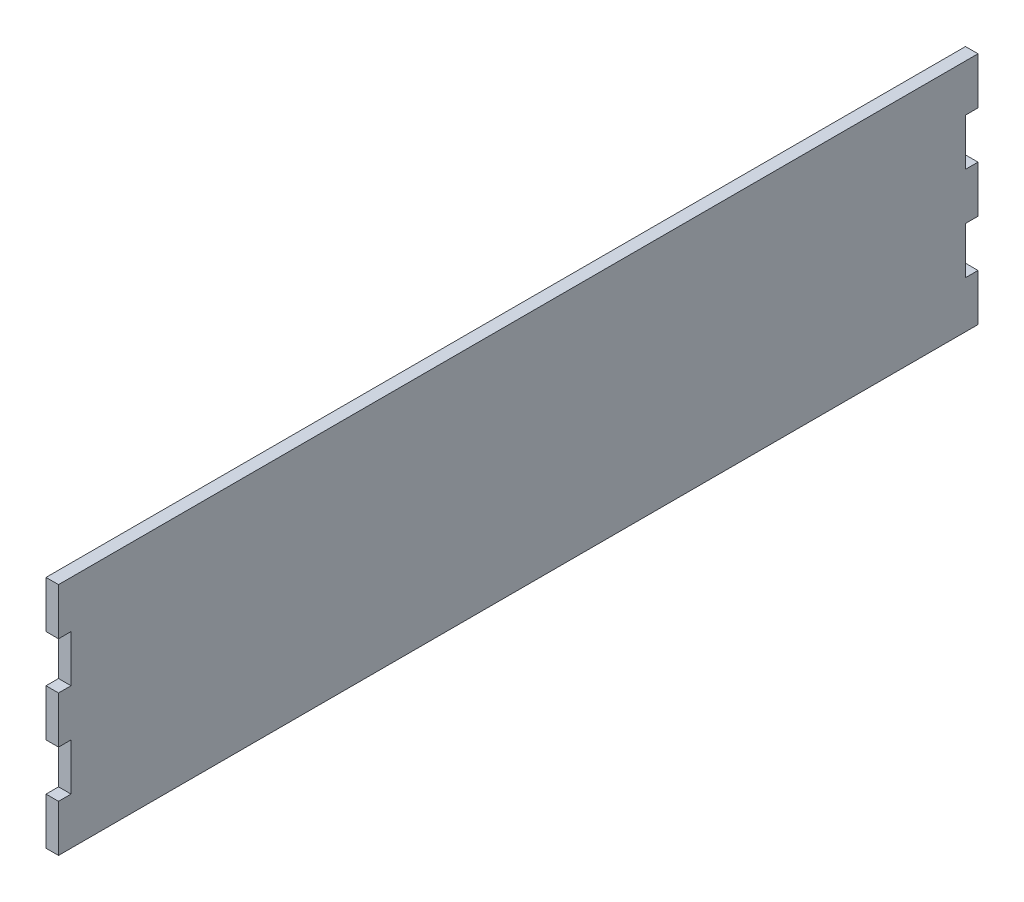
SolidWorks part; units mm, degrees
ref_plane "Front Plane" through (0, 0, 0) normal (0, 0, 1) x (1, 0, 0)
ref_plane "Top Plane" through (0, 0, 0) normal (0, 1, 0) x (1, 0, 0)
ref_plane "Right Plane" through (0, 0, 0) normal (1, 0, 0) x (0, 0, -1)
sketch "Sketch1" plane through (0, 0, 0) normal (1, 0, 0) x (0, 0, -1)
  line L0 (0, 37.2518) -> (0, -37.7482) construction
  line L1 (-147, 37.2518) -> (147, 37.2518)
  line L2 (-147, 37.2518) -> (-147, 22.2518)
  line L3 (-147, -37.7482) -> (147, -37.7482)
  line L5 (-143, 22.2518) -> (-143, 7.2518)
  line L6 (-147, 22.2518) -> (-143, 22.2518)
  line L7 (-147, 7.2518) -> (-143, 7.2518)
  line L8 (-147, -7.7482) -> (-143, -7.7482)
  line L9 (-147, -22.7482) -> (-143, -22.7482)
  line L10 (-147, -22.7482) -> (-147, -37.7482)
  line L11 (-147, 7.2518) -> (-147, -7.7482)
  line L12 (-143, -7.7482) -> (-143, -22.7482)
  line L13 (143, -7.7482) -> (143, -22.7482)
  line L14 (147, 7.2518) -> (147, -7.7482)
  line L15 (147, -22.7482) -> (147, -37.7482)
  line L16 (147, -22.7482) -> (143, -22.7482)
  line L17 (147, -7.7482) -> (143, -7.7482)
  line L18 (147, 7.2518) -> (143, 7.2518)
  line L19 (147, 22.2518) -> (143, 22.2518)
  line L20 (143, 22.2518) -> (143, 7.2518)
  line L21 (147, 37.2518) -> (147, 22.2518)
  point P0 (0, 0)
  dimension "D1" = 147
  dimension "D2" = 75
  dimension "D3" = 4
  dimension "D4" = 15
extrude "Boss-Extrude1" add sketch "Sketch1" along normal blind 4
